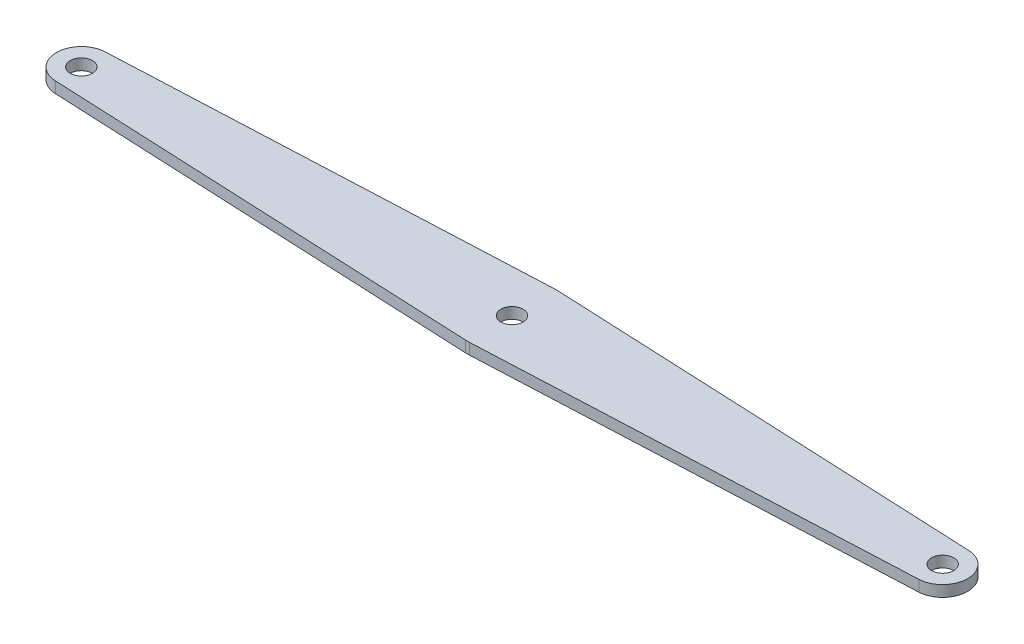
SolidWorks part; units mm, degrees
ref_plane "Спереди" through (0, 0, 0) normal (0, 0, 1) x (1, 0, 0)
ref_plane "Сверху" through (0, 0, 0) normal (0, 1, 0) x (1, 0, 0)
ref_plane "Справа" through (0, 0, 0) normal (1, 0, 0) x (0, 0, -1)
sketch "Эскиз1" plane through (0, 0, 0) normal (0, 1, 0) x (1, 0, 0)
  line L0 (-77.5, 0) -> (77.5, 0) construction
  line L1 (-77.7032, 4.4954) -> (-0.3613, 7.9918)
  line L2 (-77.7032, -4.4954) -> (-0.3613, -7.9918)
  line L3 (0.3613, 7.9918) -> (77.7032, 4.4954)
  line L4 (-0.3613, -7.9918) -> (0.3613, -7.9918)
  line L5 (77.7032, -4.4954) -> (0.3613, -7.9918)
  line L6 (-0.3613, 7.9918) -> (0.3613, 7.9918)
  arc A0 (0.3613, 7.9918) -> (-0.3613, 7.9918) centre (0, 0) ccw construction
  arc A1 (-77.7032, 4.4954) -> (-77.7032, -4.4954) centre (-77.5, 0) ccw
  arc A2 (77.7032, -4.4954) -> (77.7032, 4.4954) centre (77.5, 0) ccw
  arc A3 (-0.3613, -7.9918) -> (0.3613, -7.9918) centre (0, 0) ccw construction
  point P7 (0, 0)
  dimension "D2" = 8
  dimension "D3" = 4.5
  dimension "D1" = 155
extrude "тело" add sketch "Эскиз1" along normal blind 2
sketch "Эскиз2" plane through (0, 2, 0) normal (0, 1, 0) x (1, 0, 0)
  circle A0 centre (0, 0) radius 2
  dimension "D1" = 4
extrude "отверстие под ось вращения" cut sketch "Эскиз2" against normal through all
sketch "Эскиз3" plane through (0, 2, 0) normal (0, 1, 0) x (1, 0, 0)
  circle A0 centre (-77.5, 0) radius 2
  circle A1 centre (77.5, 0) radius 2
  dimension "D1" = 4
extrude "отверстие для крепления тягов" cut sketch "Эскиз3" against normal through all
